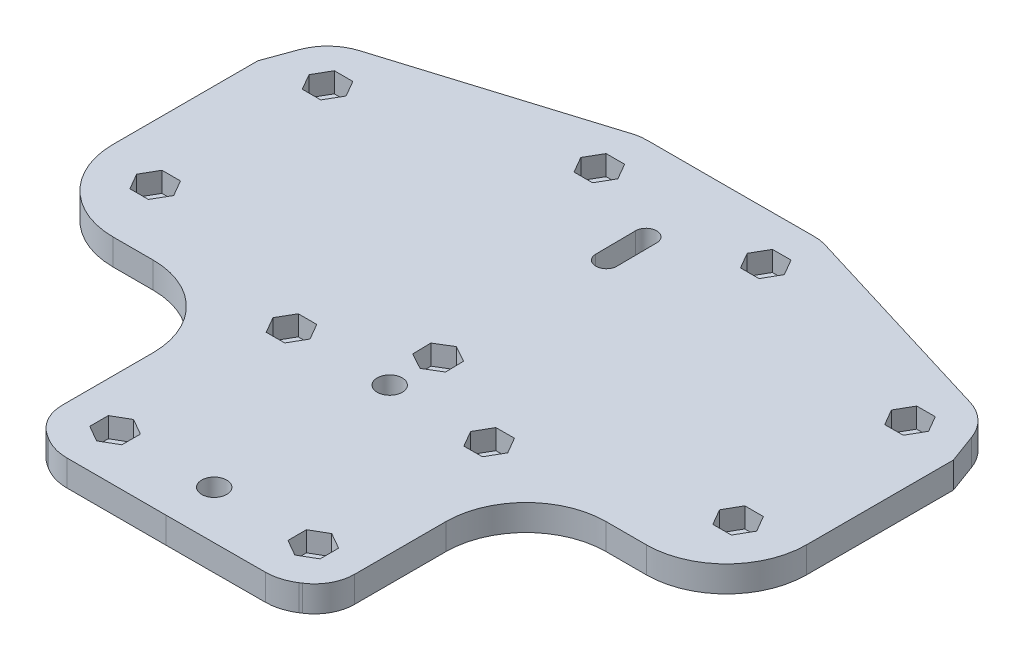
SolidWorks part; units mm, degrees
ref_plane "Front Plane" through (0, 0, 0) normal (0, 0, 1) x (1, 0, 0)
ref_plane "Top Plane" through (0, 0, 0) normal (0, 1, 0) x (1, 0, 0)
ref_plane "Right Plane" through (0, 0, 0) normal (1, 0, 0) x (0, 0, -1)
sketch "DimensionalReference" plane through (0, 0, 0) normal (0, 1, 0) x (1, 0, 0)
  line L0 (0, 0) -> (0, 54.3246) construction
  line L1 (-1000, 12.5) -> (1000, 12.5) construction
  line L2 (-1000, 12.5) -> (-1000, -12.5) construction
  line L3 (-1000, -12.5) -> (1000, -12.5) construction
  line L4 (1000, 12.5) -> (1000, -12.5) construction
  line L5 (-72.5, -22.5) -> (-72.5, 60.05) construction
  line L6 (0, 22.5) -> (0, -109.2175) construction
  line L7 (-12.5, -17.5) -> (12.9, -17.5) construction
  line L8 (-12.5, -17.5) -> (-12.5, -92.5) construction
  line L9 (-12.5, -92.5) -> (12.9, -92.5) construction
  line L10 (12.9, -17.5) -> (12.9, -92.5) construction
  line L11 (-104.4908, -32.4017) -> (-83.7785, 24.5983)
  line L12 (-23.5771, 48.153) -> (-76.0379, 31.9666)
  line L13 (-20.7123, 48.5) -> (20.7123, 48.5)
  line L14 (-93.2123, -36.5) -> (-24.5, -80.5) construction
  line L15 (-24.5, -80.5) -> (24.5, -80.5) construction
  line L16 (93.2123, -36.5) -> (24.5, -80.5) construction
  line L17 (104.4908, -32.4017) -> (83.7785, 24.5983)
  line L18 (23.5771, 48.153) -> (76.0379, 31.9666)
  line L19 (-12.5, -92.5) -> (-24.5, -92.5)
  line L20 (-99.6835, -46.6056) -> (-65.3273, -68.6056)
  line L21 (-65.3273, -68.6056) -> (-30.9712, -90.6056)
  line L22 (0.2, -92.5) -> (-12.5, -92.5)
  line L23 (99.6835, -46.6056) -> (65.3273, -68.6056)
  line L24 (65.3273, -68.6056) -> (30.9712, -90.6056)
  line L25 (12.5, -92.5) -> (24.5, -92.5)
  line L26 (-0.2, -92.5) -> (12.5, -92.5)
  circle A0 centre (0, 22.5) radius 12 construction
  circle A1 centre (-72.5, -22.5) radius 12 construction
  circle A2 centre (72.5, -22.5) radius 12 construction
  circle A3 centre (0, 22.5) radius 15 construction
  circle A4 centre (-72.5, -22.5) radius 15 construction
  circle A5 centre (72.5, -22.5) radius 15 construction
  circle A6 centre (0, 22.5) radius 25
  circle A7 centre (-72.5, -22.5) radius 25
  circle A8 centre (72.5, -22.5) radius 25
  circle A9 centre (-72.5, 20.5) radius 12
  circle A10 centre (-72.5, 20.5) radius 3.25
  circle A11 centre (-93.2123, -36.5) radius 12
  circle A12 centre (-20.7123, 36.5) radius 12
  circle A13 centre (-24.5, -36.5) radius 12
  circle A16 centre (72.5, 20.5) radius 12
  circle A17 centre (93.2123, -36.5) radius 12
  circle A18 centre (24.5, -36.5) radius 12
  circle A19 centre (20.7123, 36.5) radius 12
  circle A20 centre (-24.5, -80.5) radius 12
  circle A21 centre (24.5, -80.5) radius 12
  circle A22 centre (-58.8562, -58.5) radius 12
  circle A23 centre (58.8562, -58.5) radius 12
  point P0 (0, 0)
  point P24 (0, -262.4926)
  point P39 (0, 48.5)
  point P47 (0, -48.5)
  dimension "D3" = 24
  dimension "D10" = 24
  dimension "D11" = 24
  dimension "D13" = 30
  dimension "D14" = 30
  dimension "D15" = 30
  dimension "D16" = 50
  dimension "D17" = 50
  dimension "D18" = 50
  dimension "D19" = 24
  dimension "D21" = 6.5
  dimension "D22" = 24
  dimension "D29" = 24
  dimension "D31" = 12
  dimension "D32" = 12
  dimension "D1" = 2000
  dimension "D2" = 25
  dimension "D4" = 22.5
  dimension "D5" = 12.5
  dimension "D6" = 1000
  dimension "D7" = 145
  dimension "D8" = 72.5
  dimension "D9" = 22.5
  dimension "D12" = 22.5
  dimension "D20" = 8
  dimension "D23" = 24
  dimension "D24" = 24
  dimension "D25" = 25.4
  dimension "D26" = 75
  dimension "D27" = 12.5
  dimension "D28" = 5
  dimension "D30" = 12
sketch "Sketch2" plane through (0, 0, 0) normal (0, 1, 0) x (1, 0, 0)
  line L0 (24.8999, -92.4299) -> (0.2, -92.5)
  line L1 (-104.4908, -32.4017) -> (-83.7785, 24.5983)
  line L2 (-76.0379, 31.9666) -> (-24.9114, 47.7413)
  line L3 (0, 48.5) -> (-20.7123, 48.5)
  line L4 (-99.6835, -46.6056) -> (-30.9712, -90.6056)
  line L5 (0, 48.5) -> (0.2, -92.5) construction
  line L6 (-24.5, -92.5) -> (0.2, -92.5)
  line L7 (99.9529, -46.3225) -> (31.3657, -90.5172)
  line L8 (0, 48.5) -> (20.7122, 48.5588)
  line L9 (76.0845, 32.1824) -> (24.9134, 47.812)
  line L10 (104.7199, -32.1049) -> (83.8459, 24.8361)
  line L11 (-0.044, 27.5) -> (0.044, 17.5) construction
  line L12 (2.5809, 27.5231) -> (2.6689, 17.5231)
  line L13 (-2.6689, 27.4769) -> (-2.5809, 17.4769)
  line L28 (-24.5, -36.5) -> (24.5, -36.5) construction
  line L29 (-24.5, -80.5) -> (24.8659, -80.43) construction
  line L30 (0, 0) -> (139.3739, 0) construction
  arc A0 (-20.7123, 48.5) -> (-24.9114, 47.7413) centre (-20.7123, 36.5) ccw
  arc A6 (-30.9712, -90.6056) -> (-24.5, -92.5) centre (-24.5, -80.5) ccw
  arc A8 (-104.4908, -32.4017) -> (-99.6835, -46.6056) centre (-93.2123, -36.5) ccw
  arc A10 (-76.0379, 31.9666) -> (-83.7785, 24.5983) centre (-72.5, 20.5) ccw
  arc A11 (104.7199, -32.1049) -> (99.9529, -46.3225) centre (93.4531, -36.2352) cw
  arc A12 (76.0845, 32.1824) -> (83.8459, 24.8361) centre (72.5791, 20.7058) cw
  arc A13 (31.3657, -90.5172) -> (24.8999, -92.4299) centre (24.8659, -80.43) cw
  arc A14 (20.7122, 48.5588) -> (24.9134, 47.812) centre (20.7463, 36.5588) cw
  circle A15 centre (-72.5, 20.5) radius 2.625
  circle A16 centre (-20.7123, 36.5) radius 2.625
  circle A17 centre (-93.2123, -36.5) radius 2.625
  circle A18 centre (-58.8562, -58.5) radius 2.625
  circle A19 centre (-24.5, -80.5) radius 2.625
  circle A20 centre (-24.5, -36.5) radius 2.625
  circle A21 centre (-72.5, -22.5) radius 2.625
  arc A23 (2.5809, 27.5231) -> (-2.6689, 27.4769) centre (-0.044, 27.5) ccw
  arc A24 (-2.5809, 17.4769) -> (2.6689, 17.5231) centre (0.044, 17.5) ccw
  circle A25 centre (24.741, -36.4302) radius 2.625
  circle A26 centre (24.8659, -80.43) radius 2.625
  circle A27 centre (59.1595, -58.3326) radius 2.625
  circle A28 centre (93.4531, -36.2352) radius 2.625
  circle A29 centre (72.7011, -22.294) radius 2.625
  circle A30 centre (72.5791, 20.7058) radius 2.625
  circle A31 centre (20.7463, 36.5588) radius 2.625
  circle A32 centre (0, -36.5) radius 3.125
  circle A33 centre (0.1829, -80.465) radius 3.125
  circle A36 centre (0.1035, -24.5) radius 2.625
  point P22 (0, 22.5)
  dimension "D1" = 5.25
  dimension "D2" = 2.625
  dimension "D6" = 6.25
  dimension "D7" = 6.25
  dimension "D4" = 5.25
  dimension "D3" = 10
  dimension "D5" = 12
extrude "MainPlate" add sketch "Sketch2" along normal blind 6.5
sketch "Sketch8" plane through (0, 6.5, 0) normal (0, 1, 0) x (1, 0, 0)
  line L0 (0, 48.5) -> (0.2, -92.5) construction
  line L7 (-3.8477, -26.8919) -> (0.1994, -29.1178)
  line L8 (0.1994, -29.1178) -> (4.1506, -26.7259)
  line L9 (-19.8812, -36.5) -> (-22.1906, -32.5)
  line L10 (-22.1906, -32.5) -> (-26.8094, -32.5)
  line L11 (-26.8094, -32.5) -> (-29.1188, -36.5)
  line L12 (-29.1188, -36.5) -> (-26.8094, -40.5)
  line L13 (-26.8094, -40.5) -> (-22.1906, -40.5)
  line L14 (-22.1906, -40.5) -> (-19.8812, -36.5)
  line L15 (-67.8812, -22.5) -> (-70.1906, -18.5)
  line L16 (-70.1906, -18.5) -> (-74.8094, -18.5)
  line L17 (-74.8094, -18.5) -> (-77.1188, -22.5)
  line L18 (-77.1188, -22.5) -> (-74.8094, -26.5)
  line L19 (-74.8094, -26.5) -> (-70.1906, -26.5)
  line L20 (-70.1906, -26.5) -> (-67.8812, -22.5)
  line L21 (-67.8812, 20.5) -> (-70.1906, 24.5)
  line L22 (-70.1906, 24.5) -> (-74.8094, 24.5)
  line L23 (-74.8094, 24.5) -> (-77.1188, 20.5)
  line L24 (-77.1188, 20.5) -> (-74.8094, 16.5)
  line L25 (-74.8094, 16.5) -> (-70.1906, 16.5)
  line L26 (-70.1906, 16.5) -> (-67.8812, 20.5)
  line L27 (-88.5935, -36.5) -> (-90.9029, -32.5)
  line L28 (-90.9029, -32.5) -> (-95.5217, -32.5)
  line L29 (-95.5217, -32.5) -> (-97.8311, -36.5)
  line L30 (-97.8311, -36.5) -> (-95.5217, -40.5)
  line L31 (-95.5217, -40.5) -> (-90.9029, -40.5)
  line L32 (-90.9029, -40.5) -> (-88.5935, -36.5)
  line L33 (-54.2374, -58.5) -> (-56.5468, -54.5)
  line L34 (-56.5468, -54.5) -> (-61.1656, -54.5)
  line L35 (-61.1656, -54.5) -> (-63.475, -58.5)
  line L36 (-63.475, -58.5) -> (-61.1656, -62.5)
  line L37 (-61.1656, -62.5) -> (-56.5468, -62.5)
  line L38 (-56.5468, -62.5) -> (-54.2374, -58.5)
  line L39 (-24.5, -75.8812) -> (-28.5, -78.1906)
  line L40 (-28.5, -78.1906) -> (-28.5, -82.8094)
  line L41 (-28.5, -82.8094) -> (-24.5, -85.1188)
  line L42 (-24.5, -85.1188) -> (-20.5, -82.8094)
  line L43 (-20.5, -82.8094) -> (-20.5, -78.1906)
  line L44 (-20.5, -78.1906) -> (-24.5, -75.8812)
  line L45 (-16.0935, 36.5) -> (-18.4029, 40.5)
  line L46 (-18.4029, 40.5) -> (-23.0217, 40.5)
  line L47 (-23.0217, 40.5) -> (-25.3311, 36.5)
  line L48 (-25.3311, 36.5) -> (-23.0217, 32.5)
  line L49 (-23.0217, 32.5) -> (-18.4029, 32.5)
  line L50 (-18.4029, 32.5) -> (-16.0935, 36.5)
  line L93 (4.1506, -26.7259) -> (4.0548, -22.1081)
  line L94 (4.0548, -22.1081) -> (0.0077, -19.8822)
  line L95 (0.0077, -19.8822) -> (-3.9435, -22.2741)
  line L96 (-3.9435, -22.2741) -> (-3.8477, -26.8919)
  line L97 (18.4482, 32.5523) -> (16.1275, 36.5457)
  line L98 (23.067, 32.5654) -> (18.4482, 32.5523)
  line L99 (25.3651, 36.5719) -> (23.067, 32.5654)
  line L100 (23.0443, 40.5653) -> (25.3651, 36.5719)
  line L101 (18.4255, 40.5522) -> (23.0443, 40.5653)
  line L102 (16.1275, 36.5457) -> (18.4255, 40.5522)
  line L103 (20.8593, -78.1319) -> (24.8528, -75.8112)
  line L104 (20.8724, -82.7507) -> (20.8593, -78.1319)
  line L105 (24.879, -85.0488) -> (20.8724, -82.7507)
  line L106 (28.8724, -82.728) -> (24.879, -85.0488)
  line L107 (28.8593, -78.1092) -> (28.8724, -82.728)
  line L108 (24.8528, -75.8112) -> (28.8593, -78.1092)
  line L109 (56.8614, -62.3391) -> (54.5407, -58.3457)
  line L110 (61.4802, -62.326) -> (56.8614, -62.3391)
  line L111 (63.7782, -58.3195) -> (61.4802, -62.326)
  line L112 (61.4575, -54.3261) -> (63.7782, -58.3195)
  line L113 (56.8387, -54.3392) -> (61.4575, -54.3261)
  line L114 (54.5407, -58.3457) -> (56.8387, -54.3392)
  line L115 (91.155, -40.2418) -> (88.8343, -36.2483)
  line L116 (95.7738, -40.2287) -> (91.155, -40.2418)
  line L117 (98.0719, -36.2221) -> (95.7738, -40.2287)
  line L118 (95.7511, -32.2287) -> (98.0719, -36.2221)
  line L119 (91.1323, -32.2418) -> (95.7511, -32.2287)
  line L120 (88.8343, -36.2483) -> (91.1323, -32.2418)
  line L121 (70.2811, 16.6993) -> (67.9604, 20.6927)
  line L122 (74.8999, 16.7124) -> (70.2811, 16.6993)
  line L123 (77.1979, 20.7189) -> (74.8999, 16.7124)
  line L124 (74.8772, 24.7123) -> (77.1979, 20.7189)
  line L125 (70.2584, 24.6992) -> (74.8772, 24.7123)
  line L126 (67.9604, 20.6927) -> (70.2584, 24.6992)
  line L127 (70.4031, -26.3006) -> (68.0823, -22.3071)
  line L128 (75.0219, -26.2875) -> (70.4031, -26.3006)
  line L129 (77.3199, -22.2809) -> (75.0219, -26.2875)
  line L130 (74.9992, -18.2875) -> (77.3199, -22.2809)
  line L131 (70.3804, -18.3006) -> (74.9992, -18.2875)
  line L132 (68.0823, -22.3071) -> (70.3804, -18.3006)
  line L133 (22.443, -40.4367) -> (20.1223, -36.4433)
  line L134 (27.0618, -40.4236) -> (22.443, -40.4367)
  line L135 (29.3598, -36.4171) -> (27.0618, -40.4236)
  line L136 (27.0391, -32.4236) -> (29.3598, -36.4171)
  line L137 (22.4203, -32.4367) -> (27.0391, -32.4236)
  line L138 (20.1223, -36.4433) -> (22.4203, -32.4367)
  circle A0 centre (0.1035, -24.5) radius 4 construction
  circle A1 centre (-24.5, -36.5) radius 4 construction
  circle A2 centre (-72.5, -22.5) radius 4 construction
  circle A3 centre (-72.5, 20.5) radius 4 construction
  circle A4 centre (-93.2123, -36.5) radius 4 construction
  circle A5 centre (-58.8562, -58.5) radius 4 construction
  circle A6 centre (-24.5, -80.5) radius 4 construction
  circle A7 centre (-20.7123, 36.5) radius 4 construction
  circle A8 centre (20.7463, 36.5588) radius 4 construction
  circle A9 centre (24.8659, -80.43) radius 4 construction
  circle A10 centre (59.1595, -58.3326) radius 4 construction
  circle A11 centre (93.4531, -36.2352) radius 4 construction
  circle A12 centre (72.5791, 20.7058) radius 4 construction
  circle A13 centre (72.7011, -22.294) radius 4 construction
  circle A14 centre (24.741, -36.4302) radius 4 construction
  dimension "D1" = 8
  dimension "D2" = 8
  dimension "D3" = 8
  dimension "D4" = 8
  dimension "D5" = 8
  dimension "D6" = 8
  dimension "D7" = 8
  dimension "D8" = 8
extrude "PressFitNuts" cut sketch "Sketch8" against normal blind 5
sketch "Sketch11" plane through (0, 0, 0) normal (0, 1, 0) x (1, 0, 0)
  line L0 (0, -4.5) -> (0, 116.15) construction
  line L1 (-111.9, 4.5) -> (-111.9, -116.15)
  line L2 (-86.5, 4.5) -> (-86.5, -19)
  line L3 (-111.9, -116.15) -> (-86.5, -116.15)
  line L4 (86.5, 4.5) -> (86.5, 44.5764)
  line L5 (-86.5, 4.5) -> (-86.5, 44.5764)
  line L6 (-86.5, 44.5764) -> (-111.9, 44.5764)
  line L7 (-111.9, 4.5) -> (-111.9, 44.5764)
  line L8 (-86.5, -116.15) -> (-36.5, -116.15)
  line L9 (-66.5, -39) -> (-56.5, -39)
  line L10 (-36.5, -116.15) -> (-36.5, -59)
  line L11 (86.5, 44.5764) -> (111.9, 44.5764)
  line L12 (111.9, 4.5) -> (111.9, 44.5764)
  line L13 (111.9, 4.5) -> (111.9, -116.15)
  line L14 (111.9, -116.15) -> (86.5, -116.15)
  line L15 (86.5, -116.15) -> (36.5, -116.15)
  line L16 (36.5, -116.15) -> (36.5, -59)
  line L17 (66.5, -39) -> (56.5, -39)
  line L18 (86.5, 4.5) -> (86.5, -19)
  circle A0 centre (-24.5, -85) radius 3.15 construction
  circle A1 centre (-72.5, -27) radius 3.15 construction
  arc A2 (-56.5, -39) -> (-36.5, -59) centre (-56.5, -59) cw
  arc A3 (-86.5, -19) -> (-66.5, -39) centre (-66.5, -19) ccw
  arc A4 (56.5, -39) -> (36.5, -59) centre (56.5, -59) ccw
  arc A5 (86.5, -19) -> (66.5, -39) centre (66.5, -19) cw
extrude "Cut-Extrude2" cut sketch "Sketch11" along normal up to surface (6.5 mm away) up to face at (20.7463, 6.5, -36.5588)
fillet "Fillet2" radius 10 2 edges at (36.5, 3.25, 87.2089) (-36.5, 3.25, 87.0652)
move or copy body "Body-Move/Copy1" [suppressed] bodies to move or copy 106
